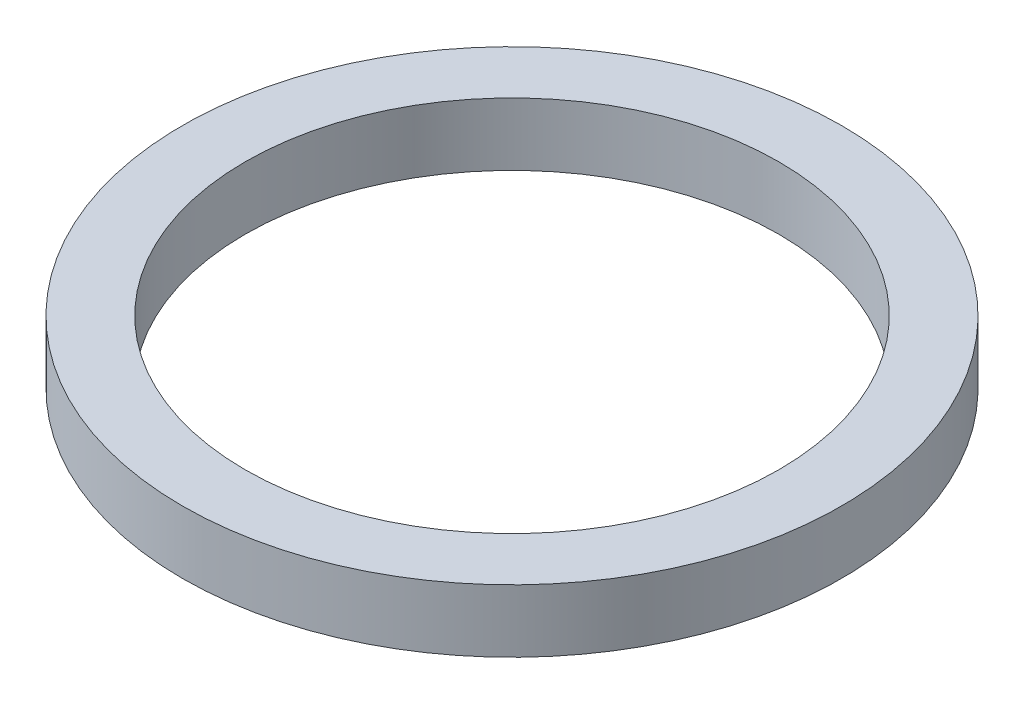
SolidWorks part; units mm, degrees
material "AISI 316 Annealed Stainless Steel Bar (SS)"
ref_plane "Front Plane" through (0, 0, 0) normal (0, 0, 1) x (1, 0, 0)
ref_plane "Top Plane" through (0, 0, 0) normal (0, 1, 0) x (1, 0, 0)
ref_plane "Right Plane" through (0, 0, 0) normal (1, 0, 0) x (0, 0, -1)
sketch "Sketch1" plane through (0, 0, 0) normal (0, 1, 0) x (1, 0, 0)
  circle A0 centre (0, 0) radius 10.5
  circle A1 centre (0, 0) radius 8.5
  dimension "D1" = 21
  dimension "D2" = 17
extrude "Boss-Extrude1" add sketch "Sketch1" along normal blind 2
